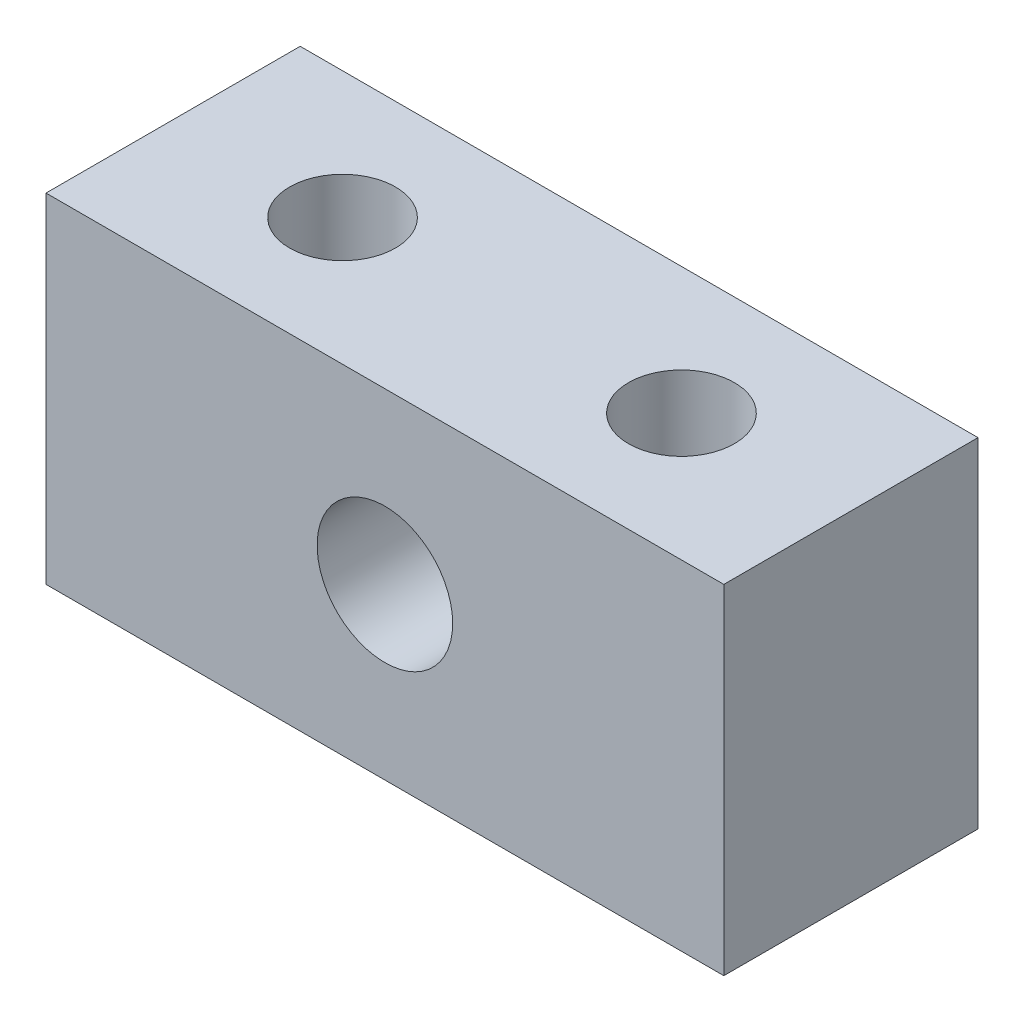
SolidWorks part; units mm, degrees
ref_plane "Plan de face" through (0, 0, 0) normal (0, 0, 1) x (1, 0, 0)
ref_plane "Plan de dessus" through (0, 0, 0) normal (0, 1, 0) x (1, 0, 0)
ref_plane "Plan de droite" through (0, 0, 0) normal (1, 0, 0) x (0, 0, -1)
sketch "Esquisse1" plane through (0, 0, 0) normal (0, 0, 1) x (1, 0, 0)
  line L1 (-6.566, 0) -> (9.434, 0)
  line L2 (-6.566, 0) -> (-6.566, 8)
  line L3 (-6.566, 8) -> (9.434, 8)
  line L4 (9.434, 0) -> (9.434, 8)
  dimension "D1" = 8
  dimension "D2" = 16
extrude "Boss.-Extru.1" add sketch "Esquisse1" along normal blind 6
hole_wizard "Trou pour taraudage pour trou taraudé M31" positions "Esquisse2" profile "Esquisse3" hole size "M3" standard "ISO" end condition through all
sketch "Esquisse2" plane through (0, 8, 0) normal (0, 1, 0) x (1, 0, 0)
  line L0 (1.434, -6) -> (1.434, 2.1897) construction
  line L1 (9.434, -6) -> (-6.566, -6) construction
  circle A0 centre (-2.566, -3) radius 1.25 construction
  point P0 (-2.566, -3)
  point P2 (5.434, -3)
sketch "Esquisse3" plane through (-2.566, 8, 3) normal (1, 0, 0) x (0, 0, 1)
  line L0 (0, 0) -> (0, 8)
  line L1 (0, 8) -> (1.25, 8)
  line L2 (1.25, 8) -> (1.25, 0)
  line L5 (1.25, 0) -> (0, 0)
  line L11 (0, -6.35) -> (0, 107.95) construction
  dimension "Diamètre du perçage jusqu'au prochain" = 2.5
  dimension "Profondeur du perçage jusqu'au prochain" = 8
sketch "Esquisse4" plane through (0, 0, 6) normal (0, 0, 1) x (1, 0, 0)
  line L1 (1.434, 0.9681) -> (1.434, 7.0802) construction
  line L2 (9.434, 0) -> (9.434, 8) construction
  line L3 (-6.566, 8) -> (-6.566, 0) construction
  line L4 (-6.566, 0) -> (9.434, 0) construction
  circle A0 centre (1.434, 4) radius 1.6
  dimension "D1" = 3.2
  dimension "D2" = 4
extrude "Enlèv. mat.-Extru.1" cut sketch "Esquisse4" against normal blind 6
